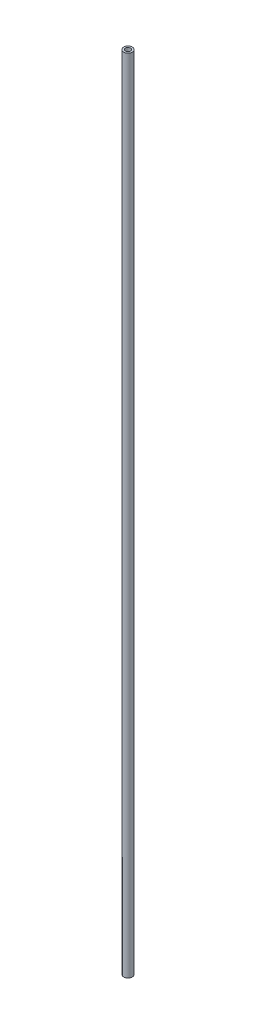
SolidWorks part; units mm, degrees
material "A-Glass Fiber"
ref_plane "Front Plane" through (0, 0, 0) normal (0, 0, 1) x (1, 0, 0)
ref_plane "Top Plane" through (0, 0, 0) normal (0, 1, 0) x (1, 0, 0)
ref_plane "Right Plane" through (0, 0, 0) normal (1, 0, 0) x (0, 0, -1)
sketch "Sketch1" plane through (0, 0, 0) normal (0, 1, 0) x (1, 0, 0)
  circle A0 centre (0, 0) radius 3
  dimension "D1" = 6
extrude "Boss-Extrude1" add sketch "Sketch1" along normal blind 550
sketch "Sketch2" plane through (0, 550, 0) normal (0, 1, 0) x (1, 0, 0)
  circle A0 centre (0, 0) radius 1.75
  dimension "D1" = 3.5
extrude "Cut-Extrude1" cut sketch "Sketch2" against normal blind 10
